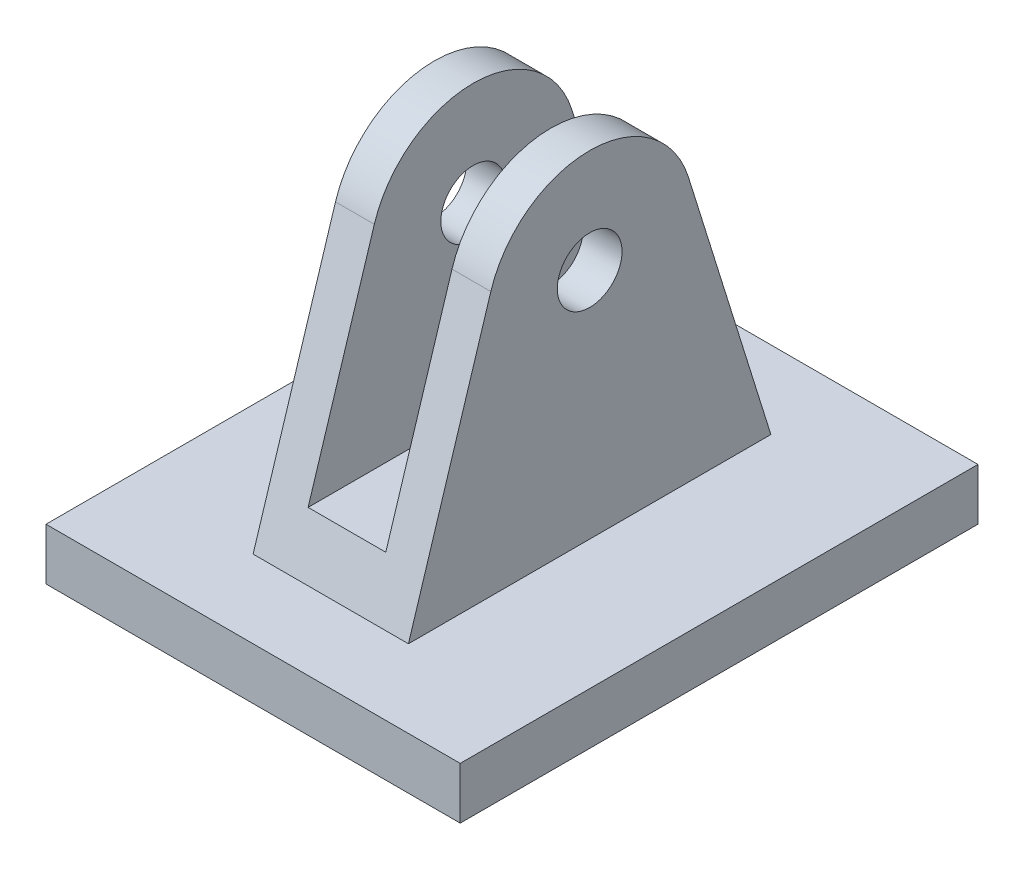
SolidWorks part; units mm, degrees
ref_plane "Front Plane" through (0, 0, 0) normal (0, 0, 1) x (1, 0, 0)
ref_plane "Top Plane" through (0, 0, 0) normal (0, 1, 0) x (1, 0, 0)
ref_plane "Right Plane" through (0, 0, 0) normal (1, 0, 0) x (0, 0, -1)
sketch "Sketch1" plane through (0, 0, 0) normal (0, 1, 0) x (1, 0, 0)
  line L1 (-40, 50) -> (40, 50)
  line L2 (-40, 50) -> (-40, -50)
  line L3 (-40, -50) -> (40, -50)
  line L4 (40, 50) -> (40, -50)
  point P4 (-40, 0)
  point P5 (0, -50)
  dimension "D1" = 80
  dimension "D2" = 100
extrude "Boss-Extrude1" add sketch "Sketch1" along normal blind 10
sketch "Sketch2" plane through (0, 0, 0) normal (1, 0, 0) x (0, 0, -1)
  line L0 (-35, 10) -> (-19.0913, 60.9599)
  line L1 (35, 10) -> (19.0913, 60.9599)
  line L2 (50, 10) -> (50, 0) construction
  line L3 (-50, 10) -> (-50, 0) construction
  line L4 (-50, 10) -> (50, 10) construction
  line L5 (-35, 10) -> (35, 10)
  arc A0 (-19.0913, 60.9599) -> (19.0913, 60.9599) centre (0, 55) cw
  circle A1 centre (0, 55) radius 6.25
  point P15 (0, 75)
  dimension "D3" = 65
  dimension "D5" = 12.5
  dimension "D4" = 20
  dimension "D1" = 15
  dimension "D2" = 15
extrude "Boss-Extrude2" add sketch "Sketch2" along normal mid plane 30
sketch "Sketch3" plane through (0, 0, 0) normal (0, 0, 1) x (1, 0, 0)
  line L0 (15, 60.9599) -> (15, 10) construction
  line L1 (-7.5, 20) -> (7.5, 20)
  line L2 (-7.5, 20) -> (-7.5, 75)
  line L3 (-7.5, 75) -> (7.5, 75)
  line L4 (7.5, 20) -> (7.5, 75)
  line L5 (-40, 10) -> (40, 10) construction
  line L6 (15, 75) -> (-15, 75) construction
  point P4 (0, 20)
  dimension "D1" = 7.5
  dimension "D2" = 10
extrude "Cut-Extrude1" cut sketch "Sketch3" against normal through all both and the other way through all
